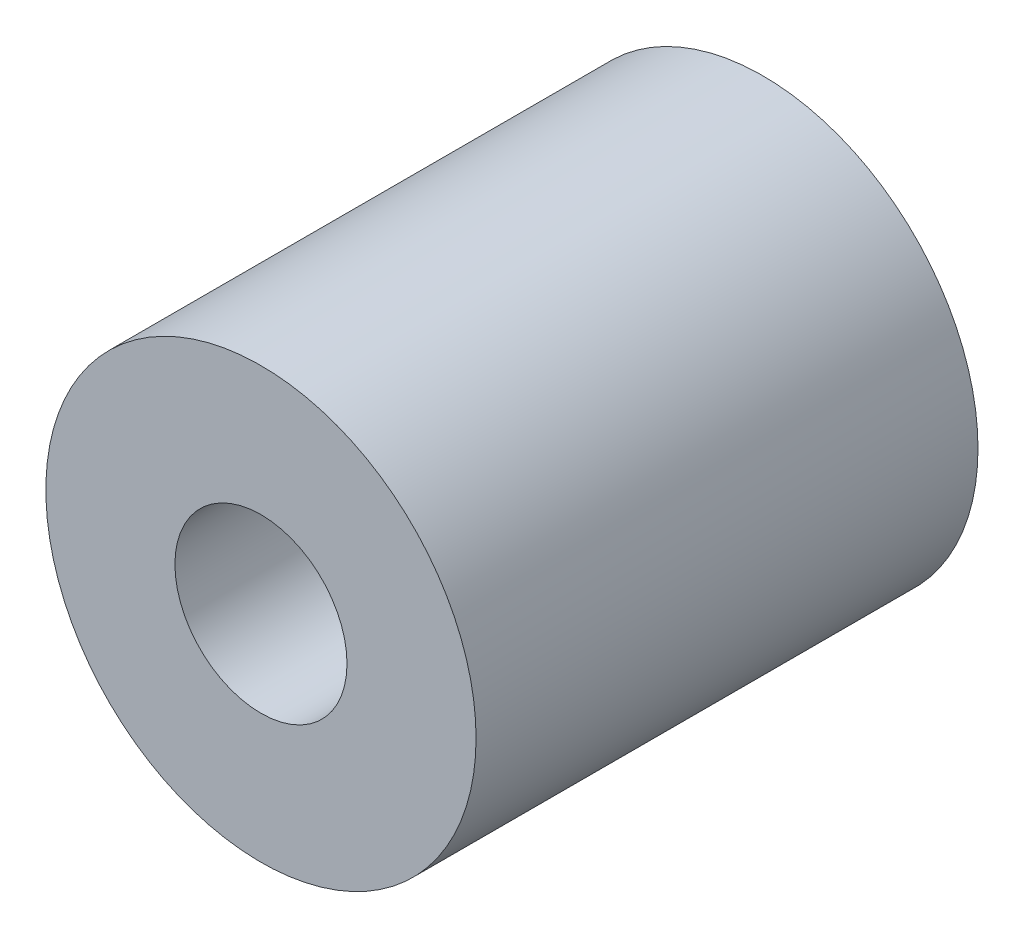
SolidWorks part; units mm, degrees
ref_plane "前视基准面" through (0, 0, 0) normal (0, 0, 1) x (1, 0, 0)
ref_plane "上视基准面" through (0, 0, 0) normal (0, 1, 0) x (1, 0, 0)
ref_plane "右视基准面" through (0, 0, 0) normal (1, 0, 0) x (0, 0, -1)
sketch "草图1" plane through (0, 0, 0) normal (0, 0, 1) x (1, 0, 0)
  circle A0 centre (0, 0) radius 15
  dimension "D1" = 30
extrude "凸台-拉伸1" add sketch "草图1" along normal blind 35
sketch "草图2" plane through (0, 0, 35) normal (0, 0, 1) x (1, 0, 0)
  circle A0 centre (0, 0) radius 6
  dimension "D1" = 12
extrude "切除-拉伸1" cut sketch "草图2" against normal blind 11.5
sketch "草图3" plane through (0, 0, 0) normal (0, 0, -1) x (-1, 0, 0)
  circle A0 centre (0, 0) radius 5
  dimension "D1" = 10
extrude "切除-拉伸2" cut sketch "草图3" against normal blind 11.5
